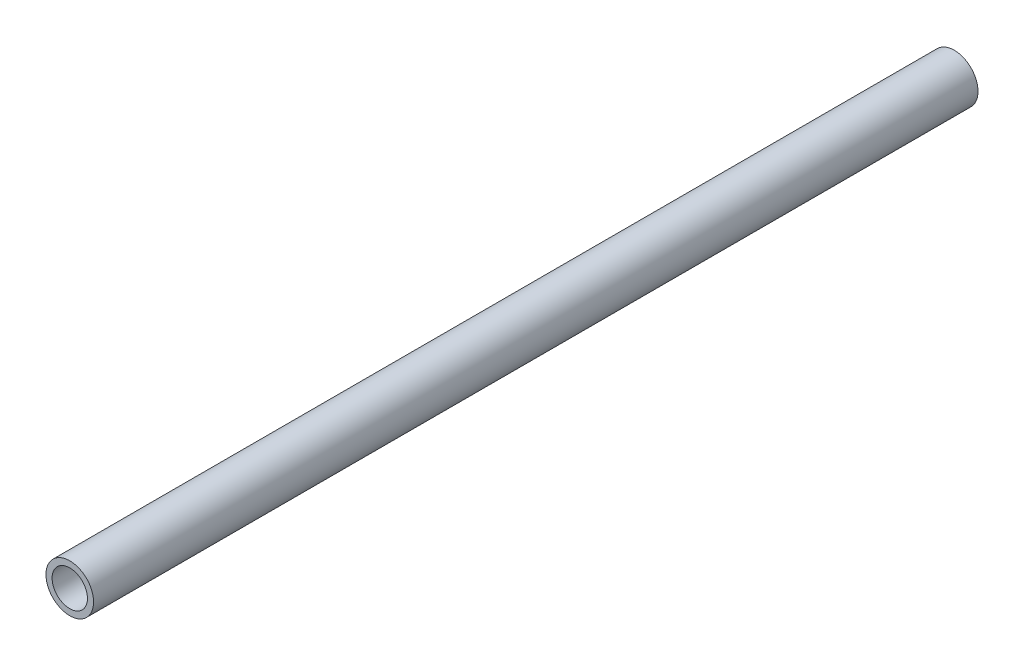
SolidWorks part; units mm, degrees
material "PVC 0.007 Plastificado"
ref_plane "Front Plane" through (0, 0, 0) normal (0, 0, 1) x (1, 0, 0)
ref_plane "Top Plane" through (0, 0, 0) normal (0, 1, 0) x (1, 0, 0)
ref_plane "Right Plane" through (0, 0, 0) normal (1, 0, 0) x (0, 0, -1)
sketch "Croquis1" plane through (0, 0, 0) normal (0, 0, 1) x (1, 0, 0)
  circle A0 centre (0, 0) radius 3.5
  circle A1 centre (0, 0) radius 2.6
  point P4 (0, 0)
  dimension "D1" = 7
  dimension "D2" = 5.2
extrude "Saliente-Extruir1" add sketch "Croquis1" along normal blind 130
